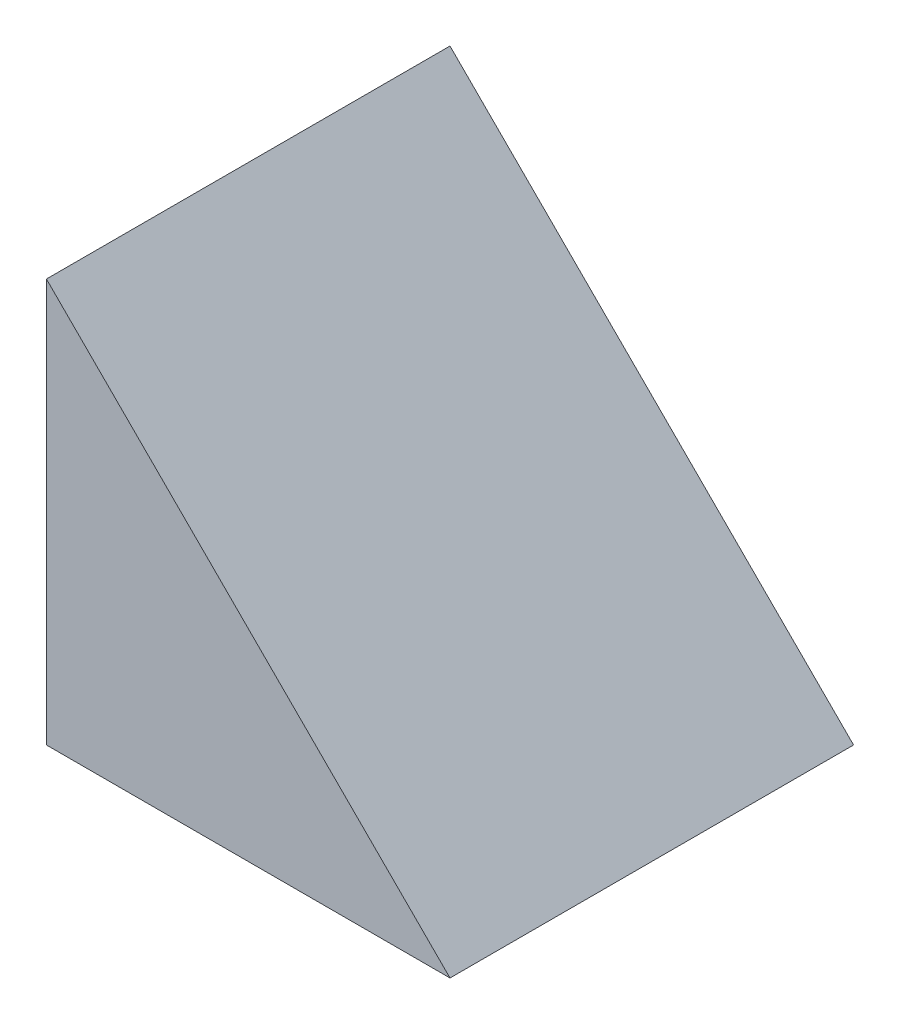
SolidWorks part; units mm, degrees
ref_plane "Front Plane" through (0, 0, 0) normal (0, 0, 1) x (1, 0, 0)
ref_plane "Top Plane" through (0, 0, 0) normal (0, 1, 0) x (1, 0, 0)
ref_plane "Right Plane" through (0, 0, 0) normal (1, 0, 0) x (0, 0, -1)
sketch "Sketch4" plane through (0, 0, 0) normal (0, 0, 1) x (1, 0, 0)
  line L0 (-429.9131, 4401.6234) -> (4570.0869, -598.3766)
  line L2 (-429.9131, 4401.6234) -> (-429.9131, -598.3766)
  line L3 (-429.9131, -598.3766) -> (4570.0869, -598.3766)
  dimension "D1" = 5000
  dimension "D2" = 5000
extrude "Boss-Extrude1" add sketch "Sketch4" along normal blind 5000
